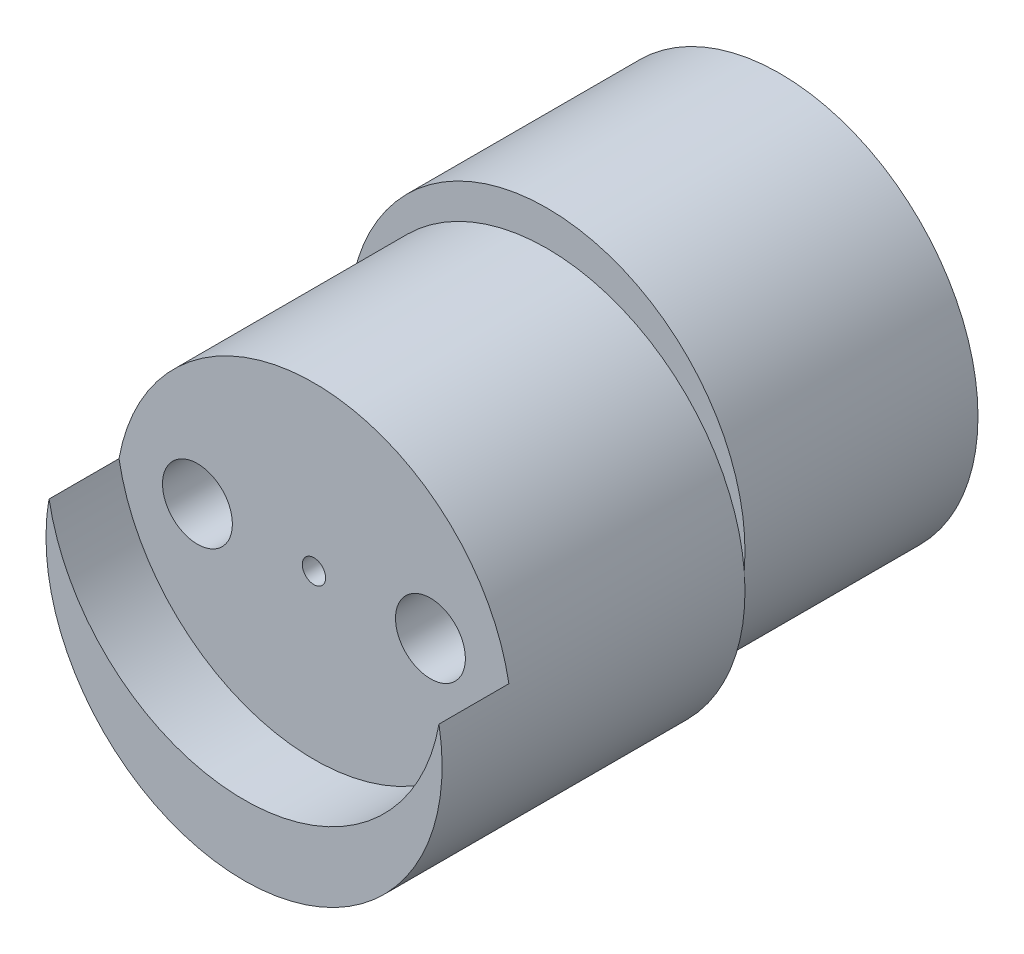
SolidWorks part; units mm, degrees
material "Custom Plastic"
ref_plane "Front Plane" through (0, 0, 0) normal (0, 0, 1) x (1, 0, 0)
ref_plane "Top Plane" through (0, 0, 0) normal (0, 1, 0) x (1, 0, 0)
ref_plane "Right Plane" through (0, 0, 0) normal (1, 0, 0) x (0, 0, -1)
sketch "Sketch1" plane through (0, 0, 0) normal (0, 0, 1) x (1, 0, 0)
  circle A0 centre (0, 0) radius 8.5
  dimension "D1" = 17
extrude "Boss-Extrude1" add sketch "Sketch1" along normal blind 10
sketch "Sketch2" plane through (0, 0, 10) normal (0, 0, 1) x (1, 0, 0)
  line L0 (0, 0) -> (0, -8.5) construction
  circle A0 centre (0, 0) radius 8.5 construction
  circle A1 centre (0, -1.5) radius 8.5
  dimension "D1" = 17
  dimension "D2" = 1.5
extrude "Boss-Extrude2" add sketch "Sketch2" along normal blind 10
sketch "Sketch4" plane through (0, 0, 20) normal (0, 0, 1) x (1, 0, 0)
  line L0 (5, 0) -> (0, 0) construction
  line L1 (0, 0) -> (-5, 0) construction
  circle A0 centre (0, 0) radius 0.5
  circle A1 centre (-5, 0) radius 1.5
  circle A2 centre (5, 0) radius 1.5
  dimension "D1" = 1
  dimension "D2" = 3
  dimension "D3" = 10
extrude "Cut-Extrude1" cut sketch "Sketch4" against normal up to surface (20 mm away) up to face at (8.5, 0, 0)
sketch "Sketch5" plane through (0, 0, 20) normal (0, 0, 1) x (1, 0, 0)
  arc A0 (-8.3666, 0) -> (8.3666, 0) centre (0, 1.5) ccw
  circle A1 centre (0, -1.5) radius 8.5 construction
  arc A2 (-8.3666, 0) -> (8.3666, 0) centre (0, -1.5) ccw
  dimension "D1" = 17
  dimension "D2" = 1.5
extrude "Boss-Extrude3" add sketch "Sketch5" along normal blind 3
